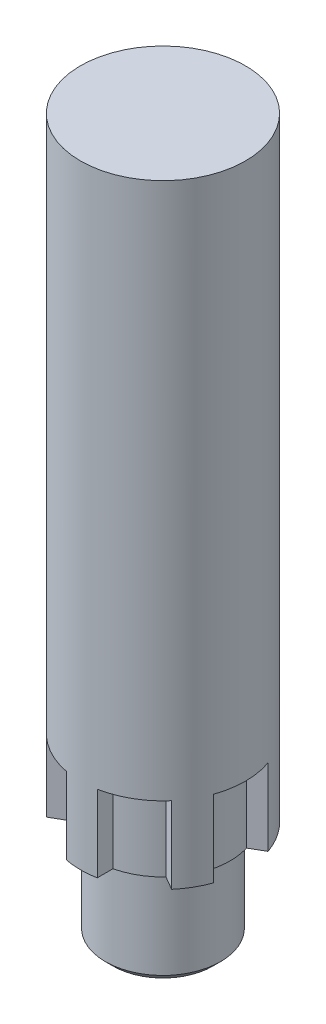
SolidWorks part; units mm, degrees
ref_plane "Front Plane" through (0, 0, 0) normal (0, 0, 1) x (1, 0, 0)
ref_plane "Top Plane" through (0, 0, 0) normal (0, 1, 0) x (1, 0, 0)
ref_plane "Right Plane" through (0, 0, 0) normal (1, 0, 0) x (0, 0, -1)
sketch "Sketch1" plane through (0, 0, 0) normal (0, 1, 0) x (1, 0, 0)
  circle A0 centre (0, 0) radius 21.5
  dimension "D1" = 43
extrude "Boss-Extrude1" add sketch "Sketch1" against normal blind 160
sketch "Sketch3" plane through (0, -160, 0) normal (0, -1, 0) x (1, 0, 0)
  line L0 (0, 0) -> (0, 21.5) construction
  line L1 (-4, 21.1246) -> (-4, 17.0367)
  line L2 (4, 21.1246) -> (4, 17.0367)
  line L3 (16.2945, 14.0264) -> (12.7542, 11.9825)
  line L4 (20.2945, 7.0982) -> (16.7542, 5.0543)
  line L5 (20.2945, -7.0982) -> (16.7542, -5.0543)
  line L6 (16.2945, -14.0264) -> (12.7542, -11.9825)
  line L7 (4, -21.1246) -> (4, -17.0367)
  line L8 (-4, -21.1246) -> (-4, -17.0367)
  line L9 (-16.2945, -14.0264) -> (-12.7542, -11.9825)
  line L10 (-20.2945, -7.0982) -> (-16.7542, -5.0543)
  line L11 (-20.2945, 7.0982) -> (-16.7542, 5.0543)
  line L12 (-16.2945, 14.0264) -> (-12.7542, 11.9825)
  arc A0 (-4, 17.0367) -> (-12.7542, 11.9825) centre (0, 0) ccw
  circle A1 centre (0, 0) radius 21.5 construction
  arc A2 (-16.7542, 5.0543) -> (-16.7542, -5.0543) centre (0, 0) ccw
  arc A3 (-12.7542, -11.9825) -> (-4, -17.0367) centre (0, 0) ccw
  arc A4 (4, -17.0367) -> (12.7542, -11.9825) centre (0, 0) ccw
  arc A5 (16.7542, -5.0543) -> (16.7542, 5.0543) centre (0, 0) ccw
  arc A6 (12.7542, 11.9825) -> (4, 17.0367) centre (0, 0) ccw
  arc A7 (-20.2945, 7.0982) -> (-20.2945, -7.0982) centre (0, 0) ccw
  arc A8 (0, 21.5) -> (-16.2945, 14.0264) centre (0, 0) ccw
  arc A9 (16.2945, 14.0264) -> (4, 21.1246) centre (0, 0) ccw
  arc A10 (20.2945, -7.0982) -> (20.2945, 7.0982) centre (0, 0) ccw
  arc A11 (4, -21.1246) -> (16.2945, -14.0264) centre (0, 0) ccw
  arc A12 (-16.2945, -14.0264) -> (-4, -21.1246) centre (0, 0) ccw
  point P32 (0, 0)
  circle M14 centre (0, 0) radius 21.5
  dimension "D1" = 35
  dimension "D2" = 4
  dimension "D3" = 6
extrude "Cut-Extrude1" cut sketch "Sketch3" against normal blind 20 contours A0 L1 L12 M14 | A6 L3 L2 M14 | A5 L5 L4 M14 | A2 L11 L10 M14 | A3 L9 L8 M14 | A4 L7 L6 M14
sketch "Sketch4" plane through (0, -160, 0) normal (0, -1, 0) x (1, 0, 0)
  circle A0 centre (0, 0) radius 15
  dimension "D1" = 30
extrude "Boss-Extrude2" add sketch "Sketch4" along normal blind 26
chamfer "Chamfer1" distance 2 angle 45 1 edges at (0, -186, -15)
